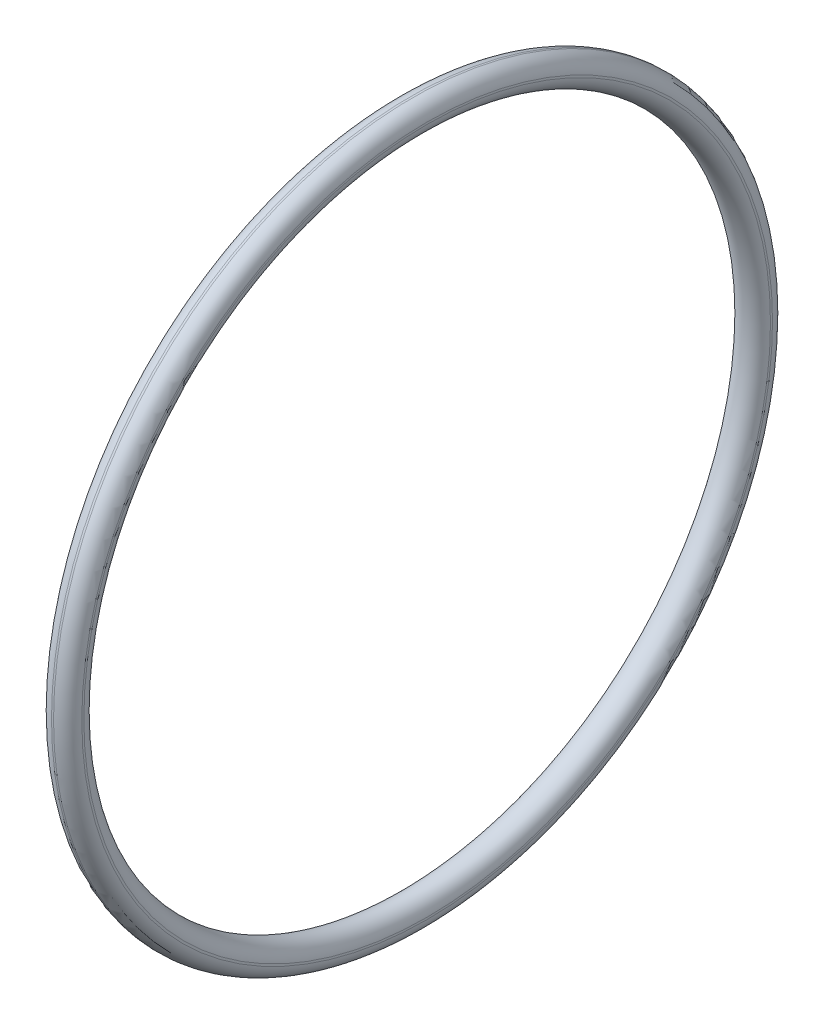
SolidWorks part; units mm, degrees
material "72NBR872 (2)"
ref_plane "Vorne" through (0, 0, 0) normal (0, 0, 1) x (1, 0, 0)
ref_plane "Oben" through (0, 0, 0) normal (0, 1, 0) x (1, 0, 0)
ref_plane "Rechts" through (0, 0, 0) normal (1, 0, 0) x (0, 0, -1)
sketch "Skizze1" plane through (0, 0, 0) normal (0, 0, 1) x (1, 0, 0)
  line L0 (0, 0) -> (14.8056, 0) construction
  line L1 (-0.1, 35.4967) -> (0.1, 35.4967)
  line L2 (1.4967, 33.9) -> (1.4967, 34.1)
  arc A0 (-0.1, 35.4967) -> (1.4967, 33.9) centre (0, 34) ccw
  arc A1 (1.4967, 34.1) -> (0.1, 35.4967) centre (0, 34) ccw
  dimension "D1" = 3
  dimension "D2" = 65
  dimension "D3" = 0.2
revolve "Rotation1" add sketch "Skizze1" angle 360 about L0
